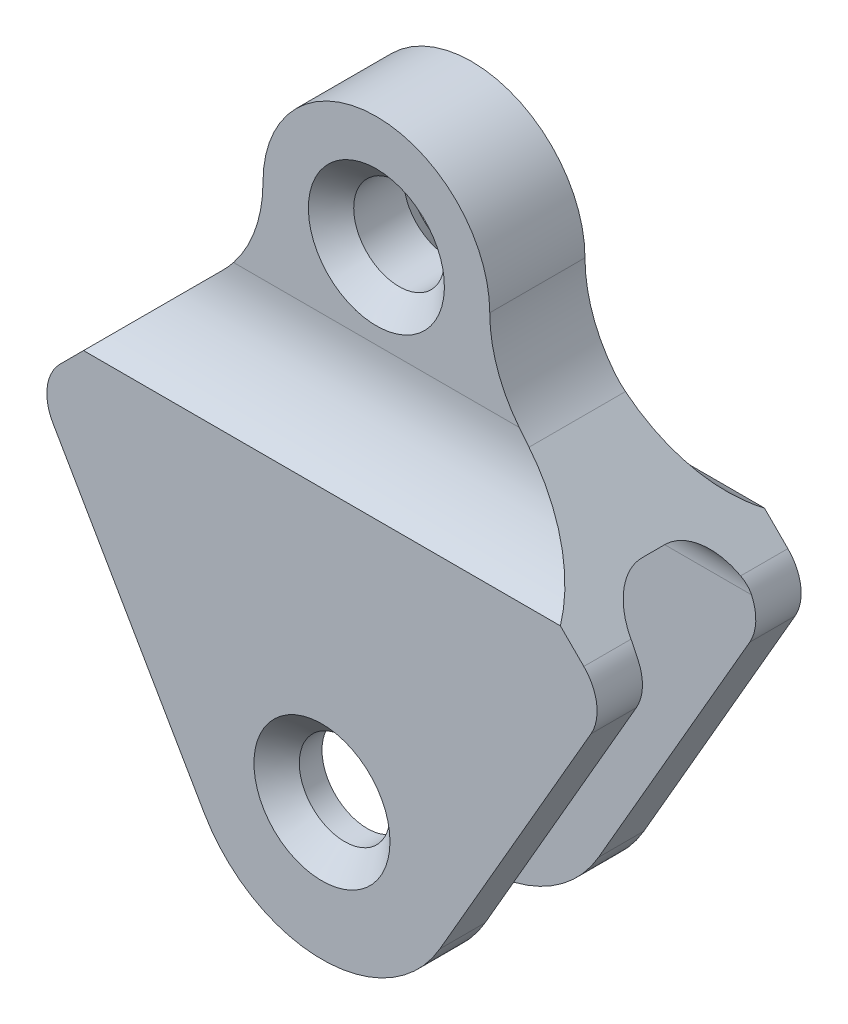
SolidWorks part; units mm, degrees
material "Titanium Ti-8Mn, Annealed"
ref_plane "Front Plane" through (0, 0, 0) normal (0, 0, 1) x (1, 0, 0)
ref_plane "Top Plane" through (0, 0, 0) normal (0, 1, 0) x (1, 0, 0)
ref_plane "Right Plane" through (0, 0, 0) normal (1, 0, 0) x (0, 0, -1)
sketch "Sketch1" plane through (0, 0, 0) normal (0, 0, 1) x (1, 0, 0)
  line L0 (-57.7405, 54.8331) -> (-33.7868, 78.7868)
  line L3 (33.7868, 78.7868) -> (57.7405, 54.8331)
  line L4 (-25.9808, -15) -> (-59.3297, 42.762)
  line L5 (25.9808, -15) -> (59.3297, 42.762)
  arc A1 (-33.7868, 78.7868) -> (-25, 100) centre (-55, 100) ccw
  arc A2 (-25, 100) -> (25, 100) centre (0, 100) cw
  arc A3 (25, 100) -> (33.7868, 78.7868) centre (55, 100) ccw
  circle A4 centre (0, 0) radius 10
  circle A5 centre (0, 0) radius 60 construction
  circle A6 centre (0, 100) radius 10
  arc A7 (25.9808, -15) -> (-25.9808, -15) centre (0, 0) cw
  arc A8 (-59.3297, 42.762) -> (-57.7405, 54.8331) centre (-50.6694, 47.762) cw
  arc A9 (59.3297, 42.762) -> (57.7405, 54.8331) centre (50.6694, 47.762) ccw
  dimension "D1" = 120
  dimension "D2" = 20
  dimension "D5" = 25
  dimension "D7" = 30
  dimension "D8" = 20
  dimension "D9" = 10
  dimension "D4" = 100
  dimension "D6" = 90
  dimension "D10" = 20
  dimension "D3" = 60
extrude "Boss-Extrude1" add sketch "Sketch1" along normal mid plane 45
sketch "Sketch2" plane through (0, 0, 0) normal (1, 0, 0) x (0, 0, -1)
  line L1 (-2.5, 62) -> (2.5, 62)
  line L2 (-12.5, 52) -> (-12.5, -62)
  line L3 (-12.5, -62) -> (12.5, -62)
  line L4 (12.5, 52) -> (12.5, -62)
  line L5 (-12.5, 62) -> (12.5, -62) construction
  line L6 (-12.5, -62) -> (12.5, 62) construction
  line L7 (-22.5, 125) -> (-10.5, 125)
  line L8 (22.5, 125) -> (-22.5, 125) construction
  line L9 (-10.5, 125) -> (-10.5, 81.3542)
  line L10 (-22.5, 100) -> (-22.5, 78.7868) construction
  line L11 (-22.5, 60) -> (-22.5, 125)
  line L12 (0, 125) -> (0, 0) construction
  line L13 (22.5, 60) -> (22.5, 125)
  line L14 (10.5, 125) -> (10.5, 81.3542)
  line L15 (22.5, 125) -> (10.5, 125)
  arc A0 (-10.5, 81.3542) -> (-22.5, 60) centre (-35.5, 81.3542) cw
  arc A1 (10.5, 81.3542) -> (22.5, 60) centre (35.5, 81.3542) ccw
  arc A2 (2.5, 62) -> (12.5, 52) centre (2.5, 52) cw
  arc A3 (-2.5, 62) -> (-12.5, 52) centre (-2.5, 52) ccw
  point P0 (0, 0)
  dimension "D4" = 25
  dimension "D6" = 10
  dimension "D1" = 25
  dimension "D2" = 65
  dimension "D3" = 12
  dimension "D5" = 62
extrude "Cut-Extrude1" cut sketch "Sketch2" against normal through all both and the other way through all
chamfer "Chamfer1" distance 5 angle 45 4 edges at (10, 0, -22.5) (10, 0, 22.5) (0, 110, 10.5) (0, 90, -10.5)
equation "\"D7@Sketch1\"=30"
equation "\"A\"= 100"
equation "\"D4@Sketch1\"=\"A\""
